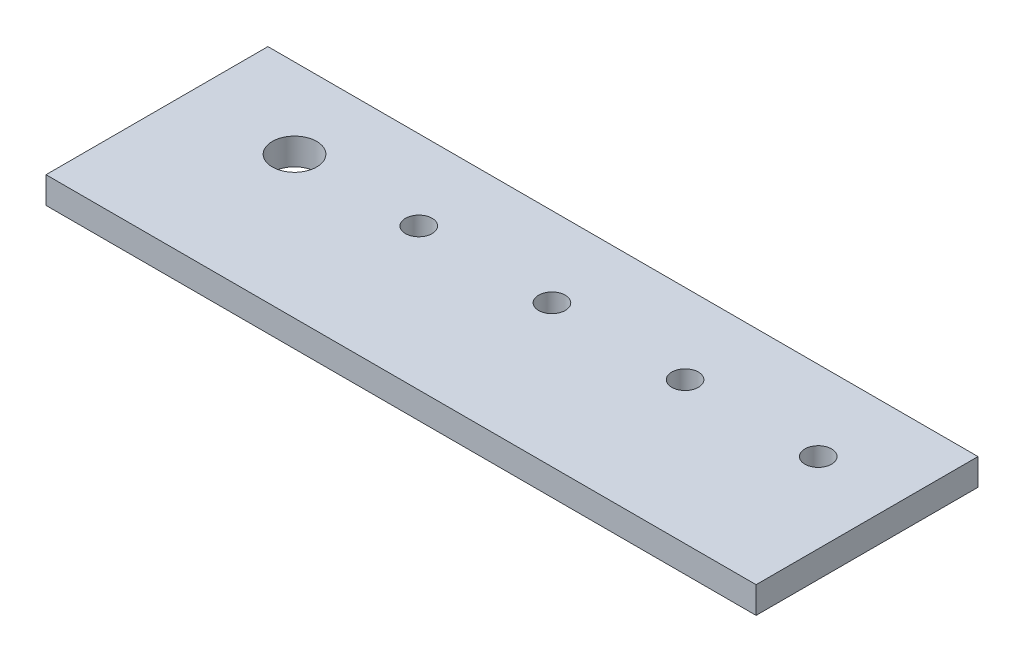
SolidWorks part; units mm, degrees
ref_plane "Front Plane" through (0, 0, 0) normal (0, 0, 1) x (1, 0, 0)
ref_plane "Top Plane" through (0, 0, 0) normal (0, 1, 0) x (1, 0, 0)
ref_plane "Right Plane" through (0, 0, 0) normal (1, 0, 0) x (0, 0, -1)
sketch "Sketch1" plane through (0, 0, 0) normal (0, 1, 0) x (1, 0, 0)
  line L1 (0, 0) -> (80, 0)
  line L2 (0, 0) -> (0, -25)
  line L3 (0, -25) -> (80, -25)
  line L4 (80, 0) -> (80, -25)
  dimension "D1" = 80
  dimension "D2" = 25
extrude "Boss-Extrude1" add sketch "Sketch1" along normal blind 3
hole_wizard "Ø3.0mm Press Dowel Hole1" positions "Sketch2" profile "Sketch3" hole size "Ø3.0" standard "ANSI Metric" end condition up to next
sketch "Sketch2" plane through (0, 3, 0) normal (0, 1, 0) x (1, 0, 0)
  line L0 (80, -25) -> (80, 0) construction
  line L1 (0, -25) -> (80, -25) construction
  point P0 (71, -9)
  point P2 (56, -9)
  point P4 (41, -9)
  point P6 (26, -9)
  dimension "D1" = 15
  dimension "D2" = 15
  dimension "D3" = 15
  dimension "D4" = 9
  dimension "D5" = 16
sketch "Sketch3" plane through (71, 3, 9) normal (1, 0, 0) x (0, 0, 1)
  line L0 (0, 0) -> (0, 3)
  line L1 (0, 3) -> (1.5, 3)
  line L2 (1.5, 3) -> (1.5, 0)
  line L5 (1.5, 0) -> (0, 0)
  line L11 (0, -6.35) -> (0, 107.95) construction
  dimension "Thru Hole Dia." = 3
  dimension "Thru Hole Depth" = 3
hole_wizard "Ø5.0mm Press Dowel Hole1" positions "Sketch4" profile "Sketch5" hole size "Ø5.0" standard "ANSI Metric" end condition up to next
sketch "Sketch4" plane through (0, 3, 0) normal (0, 1, 0) x (1, 0, 0)
  line L0 (0, 0) -> (0, -25) construction
  line L1 (0, -25) -> (80, -25) construction
  point P0 (12, -9)
  dimension "D1" = 12
  dimension "D2" = 16
sketch "Sketch5" plane through (12, 3, 9) normal (1, 0, 0) x (0, 0, 1)
  line L0 (0, 0) -> (0, 3)
  line L1 (0, 3) -> (2.5, 3)
  line L2 (2.5, 3) -> (2.5, 0)
  line L5 (2.5, 0) -> (0, 0)
  line L11 (0, -6.35) -> (0, 107.95) construction
  dimension "Thru Hole Dia." = 5
  dimension "Thru Hole Depth" = 3
